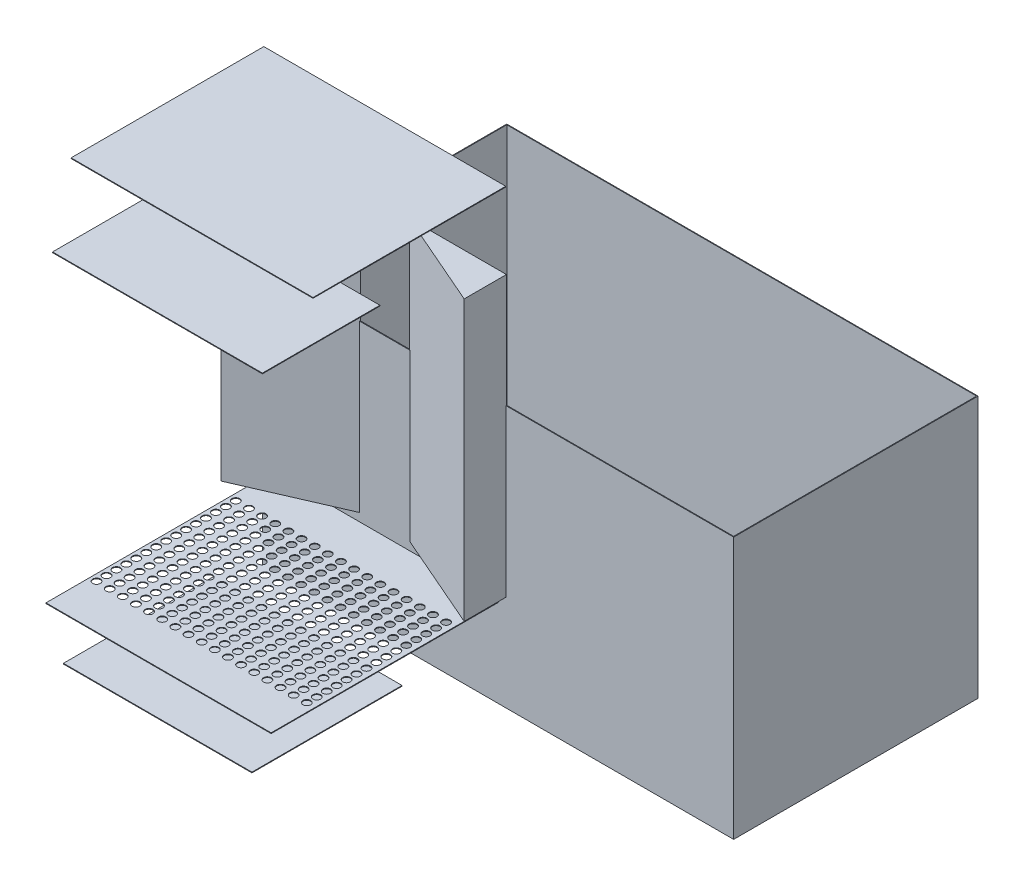
SolidWorks part; units mm, degrees
ref_plane "Спереди" through (0, 0, 0) normal (0, 0, 1) x (1, 0, 0)
ref_plane "Сверху" through (0, 0, 0) normal (0, 1, 0) x (1, 0, 0)
ref_plane "Справа" through (0, 0, 0) normal (1, 0, 0) x (0, 0, -1)
sketch "MASTER_FOOTPRINT" plane through (0, 0, 0) normal (0, 1, 0) x (1, 0, 0)
  line L1 (0, 0) -> (1350, 0)
  line L2 (0, 0) -> (0, 700)
  line L3 (0, 700) -> (1350, 700)
  line L4 (1350, 0) -> (1350, 700)
  dimension "D1" = 1350
  dimension "D2" = 700
extrude "BATH_BASE_PLATE" add sketch "MASTER_FOOTPRINT" along normal blind 750
shell "BATH_SHELL_2MM" thickness 2
sketch "Эскиз1" plane through (0, 0, 0) normal (0, 1, 0) x (1, 0, 0)
  line L1 (80, -220) -> (620, -220)
  line L2 (80, -220) -> (80, -650)
  line L3 (80, -650) -> (620, -650)
  line L4 (620, -220) -> (620, -650)
extrude "INLET_IMPACT_BAFFLE" add sketch "Эскиз1" along normal blind 2 from offset 125 separate body
sketch "Эскиз2" plane through (0, 0, 0) normal (0, 1, 0) x (1, 0, 0)
  line L0 (2, 2) -> (1348, 2) construction
  line L1 (30, 2) -> (675, 2)
  line L2 (30, 2) -> (30, -650)
  line L3 (30, -650) -> (675, -650)
  line L4 (675, 2) -> (675, -650)
  circle A0 centre (48.8235, -125) radius 11
  circle A1 centre (48.8235, -153.5) radius 11
  circle A2 centre (48.8235, -182) radius 11
  circle A3 centre (48.8235, -210.5) radius 11
  circle A4 centre (48.8235, -239) radius 11
  circle A5 centre (48.8235, -267.5) radius 11
  circle A6 centre (48.8235, -296) radius 11
  circle A7 centre (48.8235, -324.5) radius 11
  circle A8 centre (48.8235, -353) radius 11
  circle A9 centre (48.8235, -381.5) radius 11
  circle A10 centre (48.8235, -410) radius 11
  circle A11 centre (48.8235, -438.5) radius 11
  circle A12 centre (48.8235, -467) radius 11
  circle A13 centre (48.8235, -495.5) radius 11
  circle A14 centre (48.8235, -524) radius 11
  circle A15 centre (86.4706, -125) radius 11
  circle A16 centre (86.4706, -153.5) radius 11
  circle A17 centre (86.4706, -182) radius 11
  circle A18 centre (86.4706, -210.5) radius 11
  circle A19 centre (86.4706, -239) radius 11
  circle A20 centre (86.4706, -267.5) radius 11
  circle A21 centre (86.4706, -296) radius 11
  circle A22 centre (86.4706, -324.5) radius 11
  circle A23 centre (86.4706, -353) radius 11
  circle A24 centre (86.4706, -381.5) radius 11
  circle A25 centre (86.4706, -410) radius 11
  circle A26 centre (86.4706, -438.5) radius 11
  circle A27 centre (86.4706, -467) radius 11
  circle A28 centre (86.4706, -495.5) radius 11
  circle A29 centre (86.4706, -524) radius 11
  circle A30 centre (124.1176, -125) radius 11
  circle A31 centre (124.1176, -153.5) radius 11
  circle A32 centre (124.1176, -182) radius 11
  circle A33 centre (124.1176, -210.5) radius 11
  circle A34 centre (124.1176, -239) radius 11
  circle A35 centre (124.1176, -267.5) radius 11
  circle A36 centre (124.1176, -296) radius 11
  circle A37 centre (124.1176, -324.5) radius 11
  circle A38 centre (124.1176, -353) radius 11
  circle A39 centre (124.1176, -381.5) radius 11
  circle A40 centre (124.1176, -410) radius 11
  circle A41 centre (124.1176, -438.5) radius 11
  circle A42 centre (124.1176, -467) radius 11
  circle A43 centre (124.1176, -495.5) radius 11
  circle A44 centre (124.1176, -524) radius 11
  circle A45 centre (161.7647, -125) radius 11
  circle A46 centre (161.7647, -153.5) radius 11
  circle A47 centre (161.7647, -182) radius 11
  circle A48 centre (161.7647, -210.5) radius 11
  circle A49 centre (161.7647, -239) radius 11
  circle A50 centre (161.7647, -267.5) radius 11
  circle A51 centre (161.7647, -296) radius 11
  circle A52 centre (161.7647, -324.5) radius 11
  circle A53 centre (161.7647, -353) radius 11
  circle A54 centre (161.7647, -381.5) radius 11
  circle A55 centre (161.7647, -410) radius 11
  circle A56 centre (161.7647, -438.5) radius 11
  circle A57 centre (161.7647, -467) radius 11
  circle A58 centre (161.7647, -495.5) radius 11
  circle A59 centre (161.7647, -524) radius 11
  circle A60 centre (199.4118, -125) radius 11
  circle A61 centre (199.4118, -153.5) radius 11
  circle A62 centre (199.4118, -182) radius 11
  circle A63 centre (199.4118, -210.5) radius 11
  circle A64 centre (199.4118, -239) radius 11
  circle A65 centre (199.4118, -267.5) radius 11
  circle A66 centre (199.4118, -296) radius 11
  circle A67 centre (199.4118, -324.5) radius 11
  circle A68 centre (199.4118, -353) radius 11
  circle A69 centre (199.4118, -381.5) radius 11
  circle A70 centre (199.4118, -410) radius 11
  circle A71 centre (199.4118, -438.5) radius 11
  circle A72 centre (199.4118, -467) radius 11
  circle A73 centre (199.4118, -495.5) radius 11
  circle A74 centre (199.4118, -524) radius 11
  circle A75 centre (237.0588, -125) radius 11
  circle A76 centre (237.0588, -153.5) radius 11
  circle A77 centre (237.0588, -182) radius 11
  circle A78 centre (237.0588, -210.5) radius 11
  circle A79 centre (237.0588, -239) radius 11
  circle A80 centre (237.0588, -267.5) radius 11
  circle A81 centre (237.0588, -296) radius 11
  circle A82 centre (237.0588, -324.5) radius 11
  circle A83 centre (237.0588, -353) radius 11
  circle A84 centre (237.0588, -381.5) radius 11
  circle A85 centre (237.0588, -410) radius 11
  circle A86 centre (237.0588, -438.5) radius 11
  circle A87 centre (237.0588, -467) radius 11
  circle A88 centre (237.0588, -495.5) radius 11
  circle A89 centre (237.0588, -524) radius 11
  circle A90 centre (274.7059, -125) radius 11
  circle A91 centre (274.7059, -153.5) radius 11
  circle A92 centre (274.7059, -182) radius 11
  circle A93 centre (274.7059, -210.5) radius 11
  circle A94 centre (274.7059, -239) radius 11
  circle A95 centre (274.7059, -267.5) radius 11
  circle A96 centre (274.7059, -296) radius 11
  circle A97 centre (274.7059, -324.5) radius 11
  circle A98 centre (274.7059, -353) radius 11
  circle A99 centre (274.7059, -381.5) radius 11
  circle A100 centre (274.7059, -410) radius 11
  circle A101 centre (274.7059, -438.5) radius 11
  circle A102 centre (274.7059, -467) radius 11
  circle A103 centre (274.7059, -495.5) radius 11
  circle A104 centre (274.7059, -524) radius 11
  circle A105 centre (312.3529, -125) radius 11
  circle A106 centre (312.3529, -153.5) radius 11
  circle A107 centre (312.3529, -182) radius 11
  circle A108 centre (312.3529, -210.5) radius 11
  circle A109 centre (312.3529, -239) radius 11
  circle A110 centre (312.3529, -267.5) radius 11
  circle A111 centre (312.3529, -296) radius 11
  circle A112 centre (312.3529, -324.5) radius 11
  circle A113 centre (312.3529, -353) radius 11
  circle A114 centre (312.3529, -381.5) radius 11
  circle A115 centre (312.3529, -410) radius 11
  circle A116 centre (312.3529, -438.5) radius 11
  circle A117 centre (312.3529, -467) radius 11
  circle A118 centre (312.3529, -495.5) radius 11
  circle A119 centre (312.3529, -524) radius 11
  circle A120 centre (350, -125) radius 11
  circle A121 centre (350, -153.5) radius 11
  circle A122 centre (350, -182) radius 11
  circle A123 centre (350, -210.5) radius 11
  circle A124 centre (350, -239) radius 11
  circle A125 centre (350, -267.5) radius 11
  circle A126 centre (350, -296) radius 11
  circle A127 centre (350, -324.5) radius 11
  circle A128 centre (350, -353) radius 11
  circle A129 centre (350, -381.5) radius 11
  circle A130 centre (350, -410) radius 11
  circle A131 centre (350, -438.5) radius 11
  circle A132 centre (350, -467) radius 11
  circle A133 centre (350, -495.5) radius 11
  circle A134 centre (350, -524) radius 11
  circle A135 centre (387.6471, -125) radius 11
  circle A136 centre (387.6471, -153.5) radius 11
  circle A137 centre (387.6471, -182) radius 11
  circle A138 centre (387.6471, -210.5) radius 11
  circle A139 centre (387.6471, -239) radius 11
  circle A140 centre (387.6471, -267.5) radius 11
  circle A141 centre (387.6471, -296) radius 11
  circle A142 centre (387.6471, -324.5) radius 11
  circle A143 centre (387.6471, -353) radius 11
  circle A144 centre (387.6471, -381.5) radius 11
  circle A145 centre (387.6471, -410) radius 11
  circle A146 centre (387.6471, -438.5) radius 11
  circle A147 centre (387.6471, -467) radius 11
  circle A148 centre (387.6471, -495.5) radius 11
  circle A149 centre (387.6471, -524) radius 11
  circle A150 centre (425.2941, -125) radius 11
  circle A151 centre (425.2941, -153.5) radius 11
  circle A152 centre (425.2941, -182) radius 11
  circle A153 centre (425.2941, -210.5) radius 11
  circle A154 centre (425.2941, -239) radius 11
  circle A155 centre (425.2941, -267.5) radius 11
  circle A156 centre (425.2941, -296) radius 11
  circle A157 centre (425.2941, -324.5) radius 11
  circle A158 centre (425.2941, -353) radius 11
  circle A159 centre (425.2941, -381.5) radius 11
  circle A160 centre (425.2941, -410) radius 11
  circle A161 centre (425.2941, -438.5) radius 11
  circle A162 centre (425.2941, -467) radius 11
  circle A163 centre (425.2941, -495.5) radius 11
  circle A164 centre (425.2941, -524) radius 11
  circle A165 centre (462.9412, -125) radius 11
  circle A166 centre (462.9412, -153.5) radius 11
  circle A167 centre (462.9412, -182) radius 11
  circle A168 centre (462.9412, -210.5) radius 11
  circle A169 centre (462.9412, -239) radius 11
  circle A170 centre (462.9412, -267.5) radius 11
  circle A171 centre (462.9412, -296) radius 11
  circle A172 centre (462.9412, -324.5) radius 11
  circle A173 centre (462.9412, -353) radius 11
  circle A174 centre (462.9412, -381.5) radius 11
  circle A175 centre (462.9412, -410) radius 11
  circle A176 centre (462.9412, -438.5) radius 11
  circle A177 centre (462.9412, -467) radius 11
  circle A178 centre (462.9412, -495.5) radius 11
  circle A179 centre (462.9412, -524) radius 11
  circle A180 centre (500.5882, -125) radius 11
  circle A181 centre (500.5882, -153.5) radius 11
  circle A182 centre (500.5882, -182) radius 11
  circle A183 centre (500.5882, -210.5) radius 11
  circle A184 centre (500.5882, -239) radius 11
  circle A185 centre (500.5882, -267.5) radius 11
  circle A186 centre (500.5882, -296) radius 11
  circle A187 centre (500.5882, -324.5) radius 11
  circle A188 centre (500.5882, -353) radius 11
  circle A189 centre (500.5882, -381.5) radius 11
  circle A190 centre (500.5882, -410) radius 11
  circle A191 centre (500.5882, -438.5) radius 11
  circle A192 centre (500.5882, -467) radius 11
  circle A193 centre (500.5882, -495.5) radius 11
  circle A194 centre (500.5882, -524) radius 11
  circle A195 centre (538.2353, -125) radius 11
  circle A196 centre (538.2353, -153.5) radius 11
  circle A197 centre (538.2353, -182) radius 11
  circle A198 centre (538.2353, -210.5) radius 11
  circle A199 centre (538.2353, -239) radius 11
  circle A200 centre (538.2353, -267.5) radius 11
  circle A201 centre (538.2353, -296) radius 11
  circle A202 centre (538.2353, -324.5) radius 11
  circle A203 centre (538.2353, -353) radius 11
  circle A204 centre (538.2353, -381.5) radius 11
  circle A205 centre (538.2353, -410) radius 11
  circle A206 centre (538.2353, -438.5) radius 11
  circle A207 centre (538.2353, -467) radius 11
  circle A208 centre (538.2353, -495.5) radius 11
  circle A209 centre (538.2353, -524) radius 11
  circle A210 centre (575.8824, -125) radius 11
  circle A211 centre (575.8824, -153.5) radius 11
  circle A212 centre (575.8824, -182) radius 11
  circle A213 centre (575.8824, -210.5) radius 11
  circle A214 centre (575.8824, -239) radius 11
  circle A215 centre (575.8824, -267.5) radius 11
  circle A216 centre (575.8824, -296) radius 11
  circle A217 centre (575.8824, -324.5) radius 11
  circle A218 centre (575.8824, -353) radius 11
  circle A219 centre (575.8824, -381.5) radius 11
  circle A220 centre (575.8824, -410) radius 11
  circle A221 centre (575.8824, -438.5) radius 11
  circle A222 centre (575.8824, -467) radius 11
  circle A223 centre (575.8824, -495.5) radius 11
  circle A224 centre (575.8824, -524) radius 11
  circle A225 centre (613.5294, -125) radius 11
  circle A226 centre (613.5294, -153.5) radius 11
  circle A227 centre (613.5294, -182) radius 11
  circle A228 centre (613.5294, -210.5) radius 11
  circle A229 centre (613.5294, -239) radius 11
  circle A230 centre (613.5294, -267.5) radius 11
  circle A231 centre (613.5294, -296) radius 11
  circle A232 centre (613.5294, -324.5) radius 11
  circle A233 centre (613.5294, -353) radius 11
  circle A234 centre (613.5294, -381.5) radius 11
  circle A235 centre (613.5294, -410) radius 11
  circle A236 centre (613.5294, -438.5) radius 11
  circle A237 centre (613.5294, -467) radius 11
  circle A238 centre (613.5294, -495.5) radius 11
  circle A239 centre (613.5294, -524) radius 11
  circle A240 centre (651.1765, -125) radius 11
  circle A241 centre (651.1765, -153.5) radius 11
  circle A242 centre (651.1765, -182) radius 11
  circle A243 centre (651.1765, -210.5) radius 11
  circle A244 centre (651.1765, -239) radius 11
  circle A245 centre (651.1765, -267.5) radius 11
  circle A246 centre (651.1765, -296) radius 11
  circle A247 centre (651.1765, -324.5) radius 11
  circle A248 centre (651.1765, -353) radius 11
  circle A249 centre (651.1765, -381.5) radius 11
  circle A250 centre (651.1765, -410) radius 11
  circle A251 centre (651.1765, -438.5) radius 11
  circle A252 centre (651.1765, -467) radius 11
  circle A253 centre (651.1765, -495.5) radius 11
  circle A254 centre (651.1765, -524) radius 11
extrude "DISTRIBUTOR_D22" add sketch "Эскиз2" along normal blind 2 from offset 250 separate body
sketch "Эскиз3" plane through (0, 0, 0) normal (0, 1, 0) x (1, 0, 0)
  line L0 (30, -650) -> (675, -650) construction
  line L1 (48.8235, -313.5) -> (650, -313.5)
  line L2 (48.8235, -313.5) -> (48.8235, -650)
  line L3 (48.8235, -650) -> (650, -650)
  line L4 (650, -313.5) -> (650, -650)
  circle A0 centre (48.8235, -324.5) radius 11 construction
extrude "OUTLET_SUBMERGED_BAFFLE" add sketch "Эскиз3" along normal blind 2 from offset 1130 separate body
sketch "Эскиз4" plane through (0, 0, 0) normal (0, 1, 0) x (1, 0, 0)
  line L1 (2, 2) -> (695, 2)
  line L2 (2, 2) -> (2, -550)
  line L3 (2, -550) -> (695, -550)
  line L4 (695, 2) -> (695, -550)
extrude "OVERFLOW_WEIR_Z550" add sketch "Эскиз4" along normal blind 2 from offset 1290 separate body
sketch "Эскиз5" plane through (0, 0, 0) normal (0, 1, 0) x (1, 0, 0)
  line L0 (2, 1) -> (2, -120)
  line L1 (2, -120) -> (280, 1)
  line L2 (280, 1) -> (2, 1)
  line L3 (698, 1) -> (698, -120)
  line L4 (698, -120) -> (420, 1)
  line L5 (420, 1) -> (698, 1)
extrude "SLOPED_SEDIMENT_FLOOR" add sketch "Эскиз5" along normal blind 800 from offset 275
equation "\"AI_Q_Peak\"= 0.006"
equation "\"AI_B_Bath\"= 700"
equation "\"AI_L_Settle\"= 900"
equation "\"AI_L_Inlet\"= 250"
equation "\"AI_L_Outlet\"= 200"
equation "\"AI_L_Bath\"= 1350"
equation "\"AI_H_Water\"= 550"
equation "\"AI_H_Freeboard\"= 200"
equation "\"AI_H_Bath\"= 750"
equation "\"AI_Shell_Thickness\"= 2"
equation "\"AI_Inlet_DN\"= 100"
equation "\"AI_Weir_Width\"= 600"
equation "\"AI_Inlet_Baffle_Offset\"= 125"
equation "\"AI_Distributor_Open_Area\"= 0.28"
equation "\"AI_Distributor_Hole_Dia\"= 22"
equation "\"AI_Distributor_Blind_Zone\"= 110"
equation "\"AI_Outlet_Baffle_Depth\"= 250"
equation "\"AI_Screw_Diameter\"= 100"
equation "\"AI_Screw_Pitch\"= 100"
equation "\"AI_Screw_Angle\"= 30"
equation "\"AI_Screw_Rpm\"= 15"
equation "\"AI_Screw_Clearance\"= 5"
equation "\"AI_Liner_Thickness\"= 5"
equation "\"AI_Discharge_Height\"= 650"
equation "\"AI_Frame_Height\"= 500"
equation "\"D1@MASTER_FOOTPRINT\" = \"AI_L_Bath\""
equation "\"D2@MASTER_FOOTPRINT\" = \"AI_B_Bath\""
equation "\"D1@BATH_BASE_PLATE\" = \"AI_H_Bath\""
